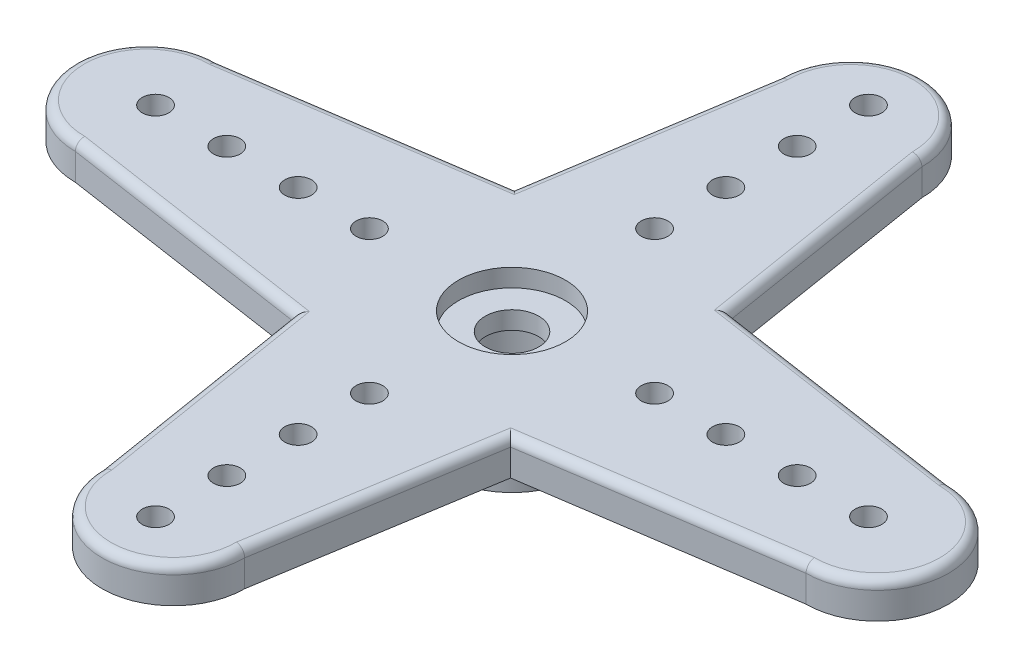
SolidWorks part; units mm, degrees
other "Camera1"
ref_plane "Front Plane" through (0, 0, 0) normal (0, 0, 1) x (1, 0, 0)
ref_plane "Top Plane" through (0, 0, 0) normal (0, 1, 0) x (1, 0, 0)
ref_plane "Right Plane" through (0, 0, 0) normal (1, 0, 0) x (0, 0, -1)
sketch "Sketch2" plane through (0, 0, 0) normal (0, 1, 0) x (1, 0, 0)
  line L2 (-4, 19) -> (-6.0276, 6.1586)
  line L3 (4, 19) -> (6.0706, 6.1579)
  line L4 (20.5, 4) -> (6.0706, 6.1579)
  line L5 (20.5, -4) -> (6.0788, -6.1567)
  line L6 (4, -19) -> (6.0788, -6.1567)
  line L7 (-4, -19) -> (-6.0914, -6.149)
  line L8 (-20.5, 4) -> (-6.0276, 6.1586)
  line L9 (-20.5, -4) -> (-6.0914, -6.149)
  arc A1 (4, 19) -> (-4, 19) centre (0, 19) ccw
  arc A2 (-20.5, 4) -> (-20.5, -4) centre (-20.5, 0) ccw
  arc A3 (20.5, -4) -> (20.5, 4) centre (20.5, 0) ccw
  arc A4 (-4, -19) -> (4, -19) centre (0, -19) ccw
  point P4 (0, 0)
  point P8 (0, 0)
  dimension "D4" = 8
  dimension "D5" = 8
  dimension "D6" = 8
  dimension "D7" = 8
  dimension "D1" = 41
  dimension "D2" = 38
extrude "Boss-Extrude1" add sketch "Sketch2" along normal blind 2
sketch "Sketch9" plane through (0, 2, 0) normal (0, 1, 0) x (1, 0, 0)
  circle A0 centre (0, 0) radius 3
  dimension "D1" = 6
extrude "Cut-Extrude1" cut sketch "Sketch9" against normal blind 1
sketch "Sketch10" plane through (0, 1, 0) normal (0, 1, 0) x (1, 0, 0)
  circle A0 centre (0, 0) radius 1.5
  dimension "D1" = 3
extrude "Cut-Extrude2" cut sketch "Sketch10" against normal blind 1
sketch "Sketch11" plane through (0, 0, 0) normal (0, -1, 0) x (1, 0, 0)
  circle A0 centre (0, 0) radius 3
  circle A1 centre (0, 0) radius 4
  dimension "D1" = 6
  dimension "D2" = 1
extrude "Boss-Extrude2" add sketch "Sketch11" along normal blind 4
sketch "Sketch12" plane through (0, 2, 0) normal (0, 1, 0) x (1, 0, 0)
  line L0 (0, 0) -> (0, 8) construction
  circle A0 centre (0, 8) radius 0.75
  circle A1 centre (0, 12) radius 0.75
  circle A2 centre (0, 16) radius 0.75
  circle A3 centre (0, 20) radius 0.75
  circle A4 centre (20, 0) radius 0.75
  circle A5 centre (16, 0) radius 0.75
  circle A6 centre (12, 0) radius 0.75
  circle A7 centre (8, 0) radius 0.75
  circle A8 centre (0, -20) radius 0.75
  circle A9 centre (0, -16) radius 0.75
  circle A10 centre (0, -12) radius 0.75
  circle A11 centre (0, -8) radius 0.75
  circle A12 centre (-20, 0) radius 0.75
  circle A13 centre (-16, 0) radius 0.75
  circle A14 centre (-12, 0) radius 0.75
  circle A15 centre (-8, 0) radius 0.75
  point P37 (0, 0)
  dimension "D2" = 1.5
  dimension "D1" = 8
  dimension "D3" = 4
  dimension "D4" = 4
extrude "Cut-Extrude3" cut sketch "Sketch12" against normal blind 4
fillet "Fillet2" radius 0.5 12 edges at (0, 2, -23) (-5.0138, 2, -12.5793) (-13.2638, 2, -5.0793) (-24.5, 2, 0) (-13.2957, 2, 5.0745) (-5.0457, 2, 12.5745) (0, 2, 23) (5.0394, 2, 12.5783) (13.2894, 2, 5.0783) (24.5, 2, 0) (13.2853, 2, -5.079) (5.0353, 2, -12.579)
fillet "Fillet3" radius 0.25 1 edges at (0, 0, 4)
